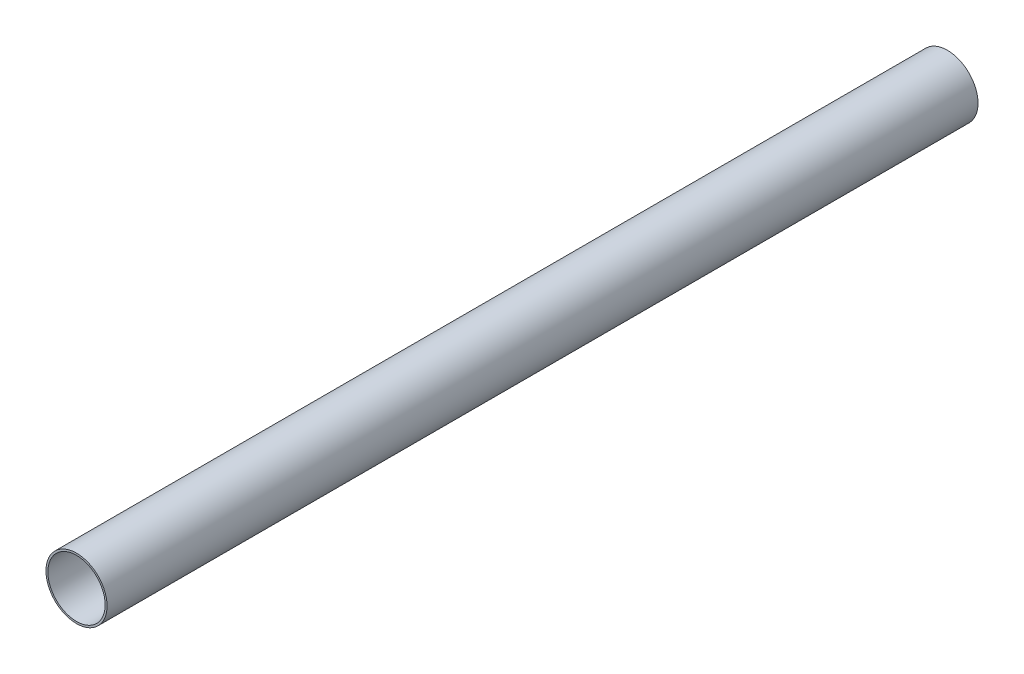
SolidWorks part; units mm, degrees
material "ABS PC"
ref_plane "Front Plane" through (0, 0, 0) normal (0, 0, 1) x (1, 0, 0)
ref_plane "Top Plane" through (0, 0, 0) normal (0, 1, 0) x (1, 0, 0)
ref_plane "Right Plane" through (0, 0, 0) normal (1, 0, 0) x (0, 0, -1)
sketch "Sketch1" plane through (0, 0, 0) normal (0, 0, 1) x (1, 0, 0)
  circle A0 centre (0, 0) radius 25.4
  circle A1 centre (0, 0) radius 23.8125
  dimension "D1" = 50.8
  dimension "D2" = 47.625
extrude "Boss-Extrude1" add sketch "Sketch1" along normal blind 723.9
